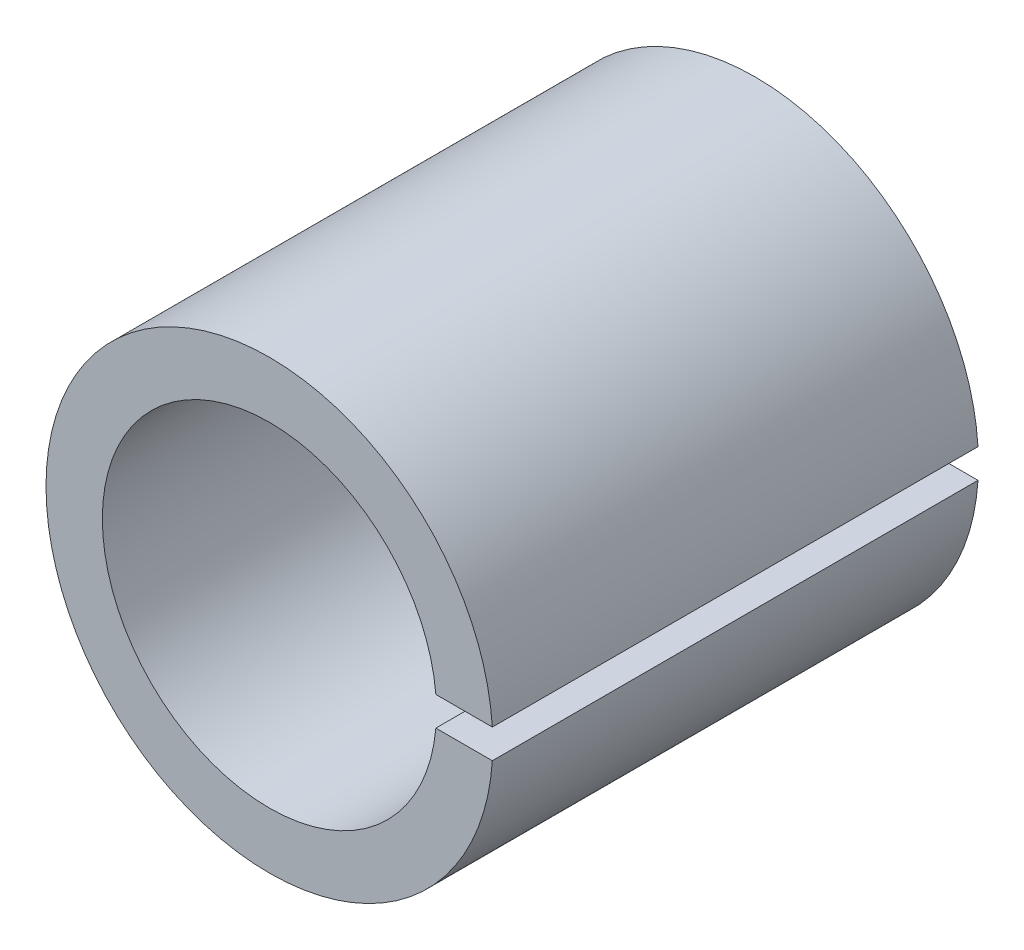
SolidWorks part; units mm, degrees
ref_plane "Front Plane" through (0, 0, 0) normal (0, 0, 1) x (1, 0, 0)
ref_plane "Top Plane" through (0, 0, 0) normal (0, 1, 0) x (1, 0, 0)
ref_plane "Right Plane" through (0, 0, 0) normal (1, 0, 0) x (0, 0, -1)
sketch "Sketch1" plane through (0, 0, 0) normal (0, 0, 1) x (1, 0, 0)
  line L0 (0, 2.1844) -> (0, 2.921) construction
  line L1 (0, -2.1844) -> (0, -2.921) construction
  line L2 (2.1761, 0.1905) -> (2.9148, 0.1905)
  line L3 (2.1761, -0.1905) -> (2.9148, -0.1905)
  arc A0 (2.9148, 0.1905) -> (2.9148, -0.1905) centre (0, 0) ccw
  arc A1 (2.1761, 0.1905) -> (2.1761, -0.1905) centre (0, 0) ccw
  dimension "D1" = 0.381
  dimension "OD" = 5.842
  dimension "ID" = 4.3688
sketch "Sketch2" plane through (0, 0, 0) normal (1, 0, 0) x (0, 0, -1)
  line L0 (-3.175, 2.1844) -> (3.175, 2.1844) construction
  line L1 (-3.175, -2.1844) -> (3.175, -2.1844) construction
  line L2 (-3.175, -2.921) -> (3.175, -2.921) construction
  line L3 (-3.175, 2.921) -> (3.175, 2.921) construction
  dimension "Length" = 6.35
extrude "Extrude1" add sketch "Sketch1" along normal up to vertex (3.175 mm away) and the other way up to vertex (3.175 mm away) up to point (0, 2.1844, 3.175) other way up to point (0, 2.1844, -3.175)
sketch "Sketch3" plane through (0, 0, 3.175) normal (0, 0, 1) x (1, 0, 0)
  circle A0 centre (0, 0) radius 2.1844 construction
  circle A3 centre (0, 0) radius 2.1844
  point P3 (-2.1844, 0)
